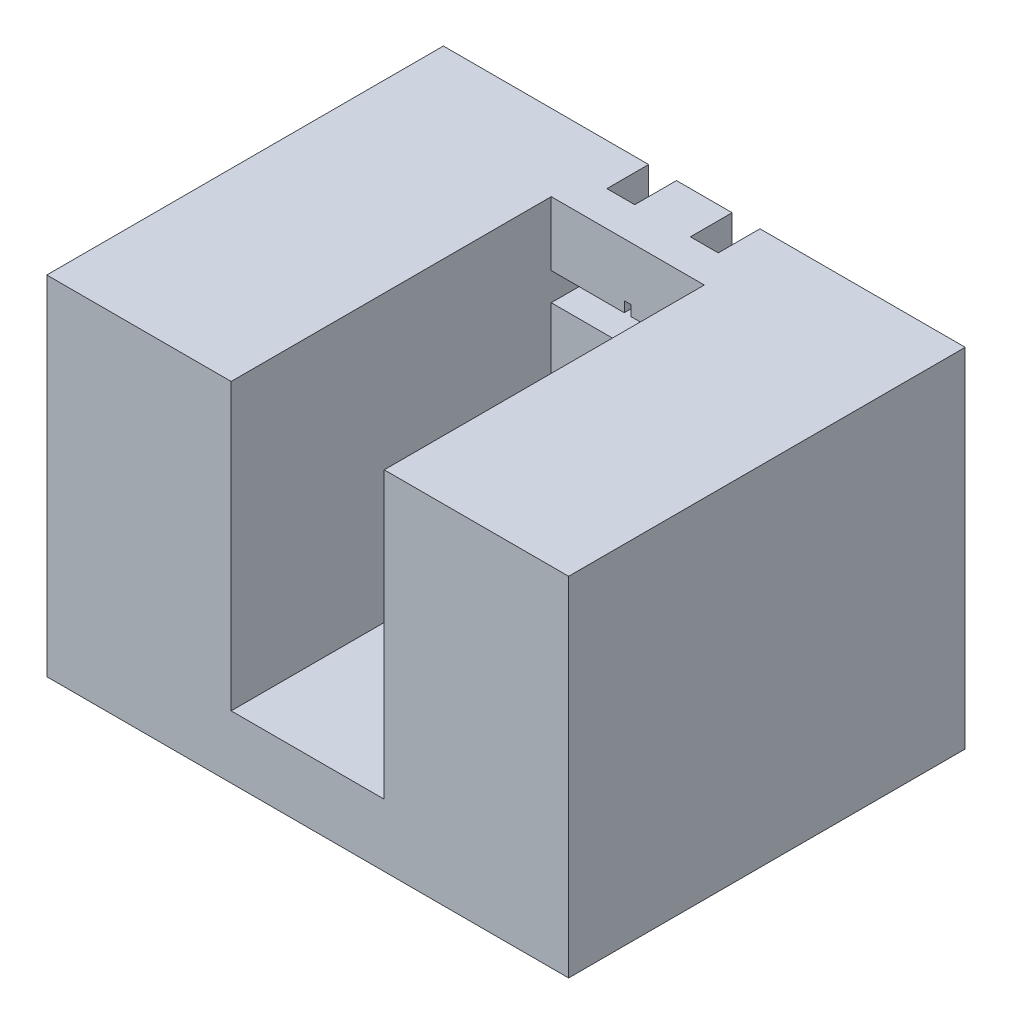
SolidWorks part; units mm, degrees
ref_plane "Front Plane" through (0, 0, 0) normal (0, 0, 1) x (1, 0, 0)
ref_plane "Top Plane" through (0, 0, 0) normal (0, 1, 0) x (1, 0, 0)
ref_plane "Right Plane" through (0, 0, 0) normal (1, 0, 0) x (0, 0, -1)
sketch "Sketch1" plane through (0, 0, 0) normal (0, 0, 1) x (1, 0, 0)
  line L1 (-37.5, -25) -> (37.5, -25)
  line L2 (-37.5, -25) -> (-37.5, 25)
  line L3 (-37.5, 25) -> (37.5, 25)
  line L4 (37.5, -25) -> (37.5, 25)
  line L5 (-37.5, -25) -> (37.5, 25) construction
  line L6 (-37.5, 25) -> (37.5, -25) construction
  point P0 (0, 0)
  dimension "D1" = 50
  dimension "D2" = 75
extrude "Boss-Extrude1" add sketch "Sketch1" along normal blind 57
sketch "Sketch2" plane through (0, 0, 57) normal (0, 0, 1) x (1, 0, 0)
  line L0 (37.5, 25) -> (-37.5, 25) construction
  line L1 (-11, 25) -> (11, 25)
  line L2 (-11, 25) -> (-11, -16)
  line L3 (-11, -16) -> (11, -16)
  line L4 (11, 25) -> (11, -16)
  point P8 (0, -16)
  dimension "D1" = 41
  dimension "D2" = 22
extrude "Cut-Extrude1" cut sketch "Sketch2" against normal offset from surface (46 mm away) 11 up to face at (0, 0, 0)
sketch "Sketch4" plane through (0, 0, 11) normal (0, 0, 1) x (1, 0, 0)
  line L0 (-11, 25) -> (-11, -16) construction
  line L1 (-11, 11.8) -> (11, 11.8)
  line L2 (-11, 11.8) -> (-11, 15.8)
  line L3 (-11, 15.8) -> (11, 15.8)
  line L4 (11, 11.8) -> (11, 15.8)
  line L5 (11, -16) -> (11, 25) construction
  line L7 (11, 25) -> (-11, 25) construction
  dimension "D1" = 9.2
  dimension "D2" = 4
extrude "Cut-Extrude2" cut sketch "Sketch4" against normal through all
sketch "Sketch5" plane through (0, 0, 0) normal (0, 0, -1) x (-1, 0, 0)
  line L0 (-37.5, 25) -> (37.5, 25) construction
  line L1 (-8, 25) -> (-4, 25)
  line L2 (-8, 25) -> (-8, 2.6)
  line L3 (-8, 2.6) -> (-4, 2.6)
  line L4 (-4, 25) -> (-4, 2.6)
  line L5 (-11, 13.8) -> (11, 13.8) construction
  line L6 (-11, 11.8) -> (-11, 15.8) construction
  line L7 (11, 15.8) -> (11, 11.8) construction
  line L9 (0, 11.8) -> (0, 25) construction
  line L10 (11, 11.8) -> (-11, 11.8) construction
  line L11 (8, 2.6) -> (4, 2.6)
  line L12 (8, 25) -> (4, 25)
  line L13 (8, 25) -> (8, 2.6)
  line L14 (4, 25) -> (4, 2.6)
  point P12 (-4, 13.8)
  dimension "D1" = 4
  dimension "D2" = 3
extrude "Cut-Extrude3" cut sketch "Sketch5" against normal blind 6
sketch "Sketch6" plane through (0, 0, 11) normal (0, 0, 1) x (1, 0, 0)
  line L0 (11, 15.8) -> (-11, 15.8) construction
  line L1 (-0.5, 17.3) -> (0.5, 17.3)
  line L2 (-0.5, 17.3) -> (-0.5, 15.8)
  line L3 (-0.5, 15.8) -> (0.5, 15.8)
  line L4 (0.5, 17.3) -> (0.5, 15.8)
  point P6 (0, 15.8)
  point P7 (0, 15.8)
  dimension "D1" = 1.5
  dimension "D2" = 1
extrude "Cut-Extrude4" cut sketch "Sketch6" against normal blind 4.5
